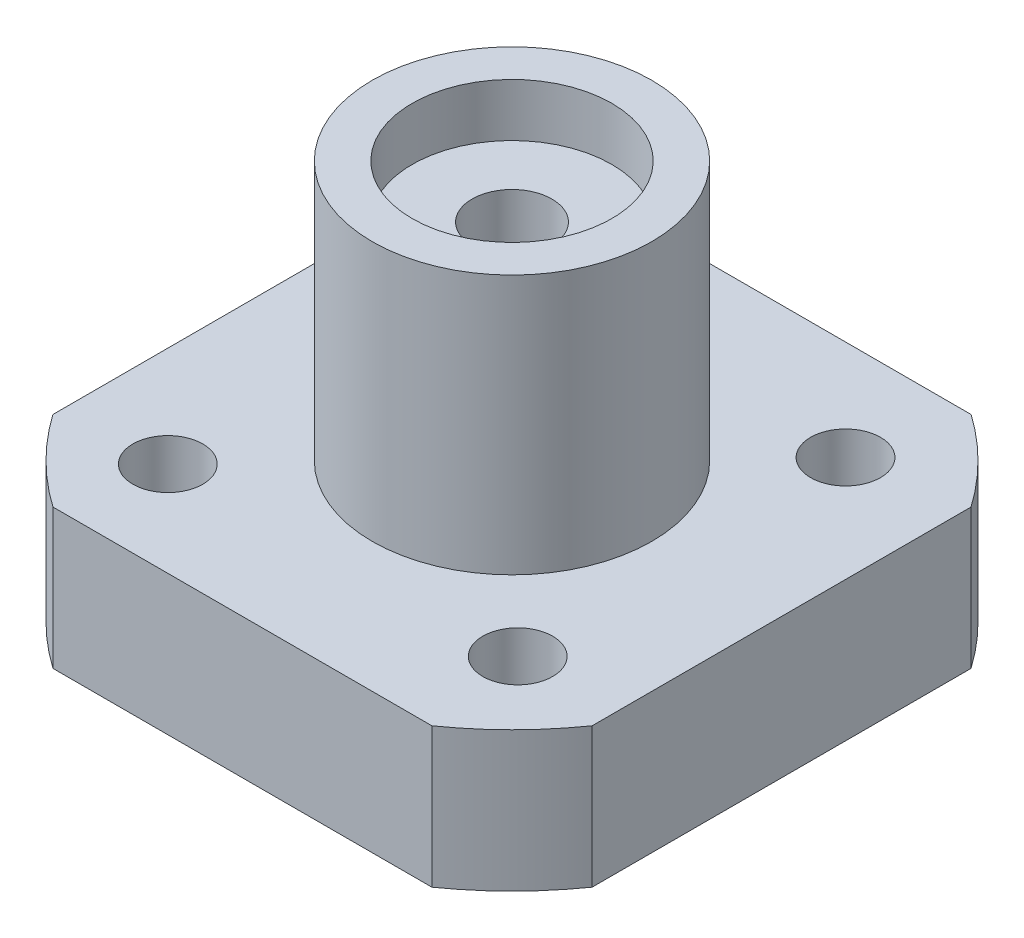
SolidWorks part; units mm, degrees
ref_plane "前视基准面" through (0, 0, 0) normal (0, 0, 1) x (1, 0, 0)
ref_plane "上视基准面" through (0, 0, 0) normal (0, 1, 0) x (1, 0, 0)
ref_plane "右视基准面" through (0, 0, 0) normal (1, 0, 0) x (0, 0, -1)
other "Configuration Table"
sketch "草图1" plane through (0, 0, 0) normal (0, 1, 0) x (1, 0, 0)
  line L1 (9.4868, -13.5) -> (-9.4868, -13.5)
  line L2 (13.5, -9.4868) -> (13.5, 9.4868)
  line L3 (9.4868, 13.5) -> (-9.4868, 13.5)
  line L4 (-13.5, -9.4868) -> (-13.5, 9.4868)
  line L5 (13.5, -13.5) -> (-11.6673, 11.6673) construction
  line L6 (13.5, 13.5) -> (-13.5, -13.5) construction
  arc A0 (-9.4868, 13.5) -> (-13.5, 9.4868) centre (0, 0) ccw
  arc A1 (-13.5, -9.4868) -> (-9.4868, -13.5) centre (0, 0) ccw
  arc A2 (9.4868, -13.5) -> (13.5, -9.4868) centre (0, 0) ccw
  arc A3 (13.5, 9.4868) -> (9.4868, 13.5) centre (0, 0) ccw
  point P0 (0, 0)
  dimension "D1" = 16.5
extrude "凸台-拉伸1" add sketch "草图1" along normal blind 7
sketch "草图3" plane through (0, 7, 0) normal (0, 1, 0) x (1, 0, 0)
  line L0 (0, 0) -> (10.1914, 10.5417) construction
  line L1 (0, 0) -> (12.6384, -12.2184) construction
  line L2 (-0.1309, -0.1354) -> (0, 0)
  circle A2 centre (-8.6264, 8.3397) radius 1.75
  circle A4 centre (8.2099, 8.4921) radius 1.75
  circle A5 centre (8.6264, -8.3397) radius 1.75
  circle A6 centre (-8.4716, -8.7628) radius 1.75
sketch "草图6" plane through (0, 7, 0) normal (0, 1, 0) x (1, 0, 0)
  circle A0 centre (0, 0) radius 7
  dimension "D1" = 14
extrude "凸台-拉伸5" add sketch "草图6" along normal blind 13 contours A0
sketch "草图8" plane through (0, 20, 0) normal (0, 1, 0) x (1, 0, 0)
  circle A0 centre (0, 0) radius 2
  dimension "D1" = 4
extrude "切除-拉伸2" cut sketch "草图8" against normal blind 30
sketch "草图9" plane through (0, 20, 0) normal (0, 1, 0) x (1, 0, 0)
  circle A1 centre (0, 0) radius 5
  dimension "D1" = 10
extrude "切除-拉伸3" cut sketch "草图9" against normal blind 2.65
sketch "草图10" plane through (0, 0, 0) normal (0, -1, 0) x (1, 0, 0)
  circle A0 centre (0, 0) radius 5
  dimension "D1" = 10
extrude "切除-拉伸4" cut sketch "草图10" against normal blind 2.65
hole_wizard "孔2" positions "草图15" profile "草图16" legacy end condition through all
sketch "草图15" plane through (0, 0, 0) normal (0, -1, 0) x (-1, 0, 0)
  point P0 (-8.2099, 8.4921)
  point P3 (8.6264, 8.3397)
  point P6 (8.4716, -8.7628)
  point P9 (-8.6264, -8.3397)
sketch "草图16" plane through (8.2099, 0, -8.4921) normal (1, 0, 0) x (0, 0, -1)
  line L0 (0, 0) -> (0, 21.0515)
  line L1 (0, 21.0515) -> (1.75, 20)
  line L2 (1.75, 20) -> (1.75, 3.1)
  line L3 (1.75, 3.1) -> (3.25, 3.1)
  line L4 (3.25, 0) -> (0, 0)
  line L5 (0, -11.3109) -> (0, 121.1557) construction
  line L6 (0, 21.0515) -> (-1.75, 20) construction
  line L7 (3.25, 3.1) -> (3.25, 0)
  dimension "直径" = 3.5
  dimension "深度" = 20
  dimension "柱坑直径" = 6.5
  dimension "柱坑深度" = 3.1
  dimension "导头角度" = 118
